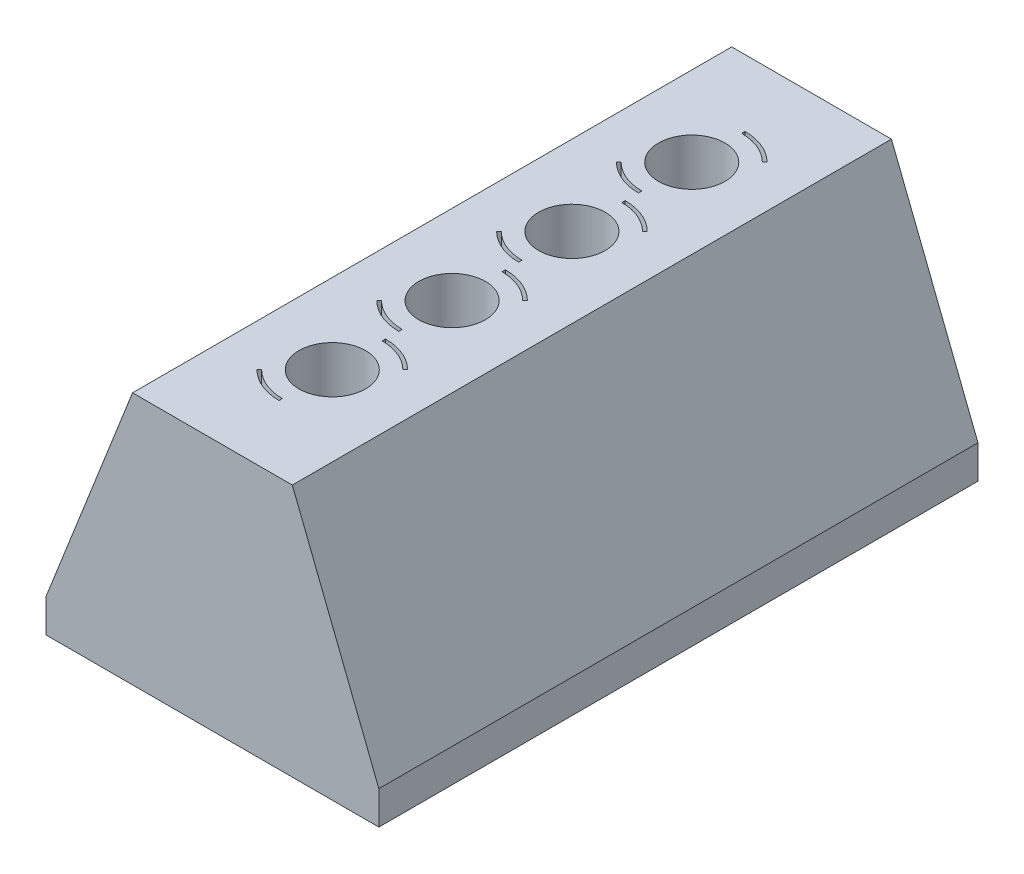
SolidWorks part; units mm, degrees
material "3.3549 (EN-AW 5182)"
ref_plane "Piano frontale" through (0, 0, 0) normal (0, 0, 1) x (1, 0, 0)
ref_plane "Piano superiore" through (0, 0, 0) normal (0, 1, 0) x (1, 0, 0)
ref_plane "Piano destro" through (0, 0, 0) normal (1, 0, 0) x (0, 0, -1)
sketch "Schizzo1" plane through (0, 0, 0) normal (0, 0, 1) x (1, 0, 0)
  line L0 (-125, 0) -> (125, 0)
  line L2 (60, 190) -> (-60, 190)
  line L4 (-125, 0) -> (-125, 25)
  line L5 (-125, 25) -> (-60, 190)
  line L6 (125, 0) -> (125, 25)
  line L7 (125, 25) -> (60, 190)
  point P2 (0, 190)
  dimension "D1" = 190
  dimension "D2" = 120
  dimension "D3" = 250
  dimension "D4" = 25
extrude "Estrusione-Estrusione1" add sketch "Schizzo1" along normal mid plane 450
sketch "Schizzo2" plane through (0, 190, 0) normal (0, 1, 0) x (1, 0, 0)
  line L0 (0, -225) -> (0, -135)
  line L1 (60, -225) -> (-60, -225) construction
  line L2 (0, -135) -> (0, -45)
  line L3 (0, -45) -> (0, 45)
  line L4 (0, 45) -> (0, 135)
  line L5 (0, 135) -> (0, 225)
  line L6 (60, 225) -> (-60, 225) construction
  circle A0 centre (0, -135) radius 25
  circle A1 centre (0, -45) radius 25
  circle A2 centre (0, 45) radius 25
  circle A3 centre (0, 135) radius 25
  dimension "D1" = 50
extrude "Taglio-Estrusione1" cut sketch "Schizzo2" against normal blind 90 contours L0 A0 L2 | L2 A0 L0 | L2 A1 L3 | L3 A1 L2 | L3 A2 L4 | L4 A2 L3 | L4 A3 L5 | L5 A3 L4
shell "Svuota1" thickness 15
sketch "Schizzo4" plane through (0, 85, 0) normal (0, -1, 0) x (1, 0, 0)
  circle A0 centre (0, -135) radius 40 construction
  circle A1 centre (0, -45) radius 40 construction
  circle A2 centre (0, 45) radius 40 construction
  circle A3 centre (0, 135) radius 40 construction
  circle A4 centre (0, -135) radius 40
  circle A5 centre (0, -45) radius 40
  circle A6 centre (0, 45) radius 40
  circle A7 centre (0, 135) radius 40
extrude "Taglio-Estrusione2" cut sketch "Schizzo4" against normal blind 20 contours A6 | A5 | A4
ref_plane "Piano1" through (0, 105, 0) normal (0, 1, 0) x (1, 0, 0)
sketch "Schizzo6" plane through (0, 105, 0) normal (0, 1, 0) x (1, 0, 0)
  line L0 (-77.3629, 210) -> (-77.3629, -225)
  line L1 (-77.3629, 210) -> (-77.3629, -225)
  line L2 (77.3629, -225) -> (77.3629, 210)
  line L3 (77.3629, -225) -> (77.3629, 210)
  line L4 (-77.3629, -225) -> (77.3629, -225)
  line L5 (-77.3629, 210) -> (77.3629, 210)
  circle A0 centre (0, 135) radius 40 construction
  circle A1 centre (0, 45) radius 40 construction
  circle A2 centre (0, -45) radius 40 construction
  circle A3 centre (0, -135) radius 40 construction
  circle A4 centre (0, 135) radius 40
  circle A5 centre (0, 45) radius 40
  circle A6 centre (0, -45) radius 40
  circle A7 centre (0, -135) radius 40
extrude "Estrusione-Estrusione2" add sketch "Schizzo6" along normal blind 10
sketch "Schizzo7" plane through (0, 0, 225) normal (0, 0, 1) x (1, 0, 0)
  line L6 (-125, 25) -> (-125, 0)
  line L7 (-125, 0) -> (125, 0)
  line L8 (125, 0) -> (125, 25)
  line L9 (125, 25) -> (60, 190)
  line L10 (60, 190) -> (-60, 190)
  line L11 (-60, 190) -> (-125, 25)
  line L12 (-125, 25) -> (-125, 0)
  line L13 (-125, 0) -> (125, 0)
  line L14 (125, 0) -> (125, 25)
  line L15 (125, 25) -> (60, 190)
  line L16 (60, 190) -> (-60, 190)
  line L17 (-60, 190) -> (-125, 25)
  dimension "D1" = 0
extrude "Estrusione-Estrusione3" add sketch "Schizzo7" against normal blind 15
sketch "Schizzo12" plane through (0, 0, -210) normal (0, 0, 1) x (1, 0, 0)
  line L0 (0, 105) -> (0, 15)
  line L1 (77.3629, 105) -> (-77.3629, 105) construction
  line L2 (-110, 15) -> (110, 15) construction
  circle A0 centre (0, 60) radius 35
  dimension "D1" = 70
extrude "Taglio-Estrusione12" cut sketch "Schizzo12" against normal through all contours L0 A0 | L0 A0
sketch "Schizzo13" plane through (0, 190, 0) normal (0, 1, 0) x (1, 0, 0)
  line L0 (0, 97.5) -> (0, 95)
  line L1 (-26.5165, 108.4835) -> (-28.2843, 106.7157)
  line L2 (26.5165, 161.5165) -> (28.2843, 163.2843)
  line L3 (0, 172.5) -> (0, 175)
  line L4 (-26.5165, 18.4835) -> (-28.2843, 16.7157)
  line L5 (0, 7.5) -> (0, 5)
  line L6 (26.5165, 71.5165) -> (28.2843, 73.2843)
  line L7 (0, 82.5) -> (0, 85)
  line L8 (-26.5165, -71.5165) -> (-28.2843, -73.2843)
  line L9 (0, -82.5) -> (0, -85)
  line L10 (26.5165, -18.4835) -> (28.2843, -16.7157)
  line L11 (0, -7.5) -> (0, -5)
  line L12 (-26.5165, -161.5165) -> (-28.2843, -163.2843)
  line L13 (0, -172.5) -> (0, -175)
  line L14 (26.5165, -108.4835) -> (28.2843, -106.7157)
  line L15 (0, -97.5) -> (0, -95)
  arc A0 (-26.5165, 108.4835) -> (0, 97.5) centre (0, 135) ccw
  arc A1 (-28.2843, 106.7157) -> (0, 95) centre (0, 135) ccw
  arc A2 (26.5165, 161.5165) -> (0, 172.5) centre (0, 135) ccw
  arc A3 (28.2843, 163.2843) -> (0, 175) centre (0, 135) ccw
  arc A4 (-26.5165, 18.4835) -> (0, 7.5) centre (0, 45) ccw
  arc A5 (-28.2843, 16.7157) -> (0, 5) centre (0, 45) ccw
  arc A6 (26.5165, 71.5165) -> (0, 82.5) centre (0, 45) ccw
  arc A7 (28.2843, 73.2843) -> (0, 85) centre (0, 45) ccw
  arc A8 (-26.5165, -71.5165) -> (0, -82.5) centre (0, -45) ccw
  arc A9 (-28.2843, -73.2843) -> (0, -85) centre (0, -45) ccw
  arc A10 (26.5165, -18.4835) -> (0, -7.5) centre (0, -45) ccw
  arc A11 (28.2843, -16.7157) -> (0, -5) centre (0, -45) ccw
  arc A12 (-26.5165, -161.5165) -> (0, -172.5) centre (0, -135) ccw
  arc A13 (-28.2843, -163.2843) -> (0, -175) centre (0, -135) ccw
  arc A14 (26.5165, -108.4835) -> (0, -97.5) centre (0, -135) ccw
  arc A15 (28.2843, -106.7157) -> (0, -95) centre (0, -135) ccw
  dimension "D1" = 75
  dimension "D2" = 80
  dimension "D3" = 45
  dimension "D5" = 4
  dimension "D4" = 2
extrude "Taglio-Estrusione13" cut sketch "Schizzo13" against normal blind 20
